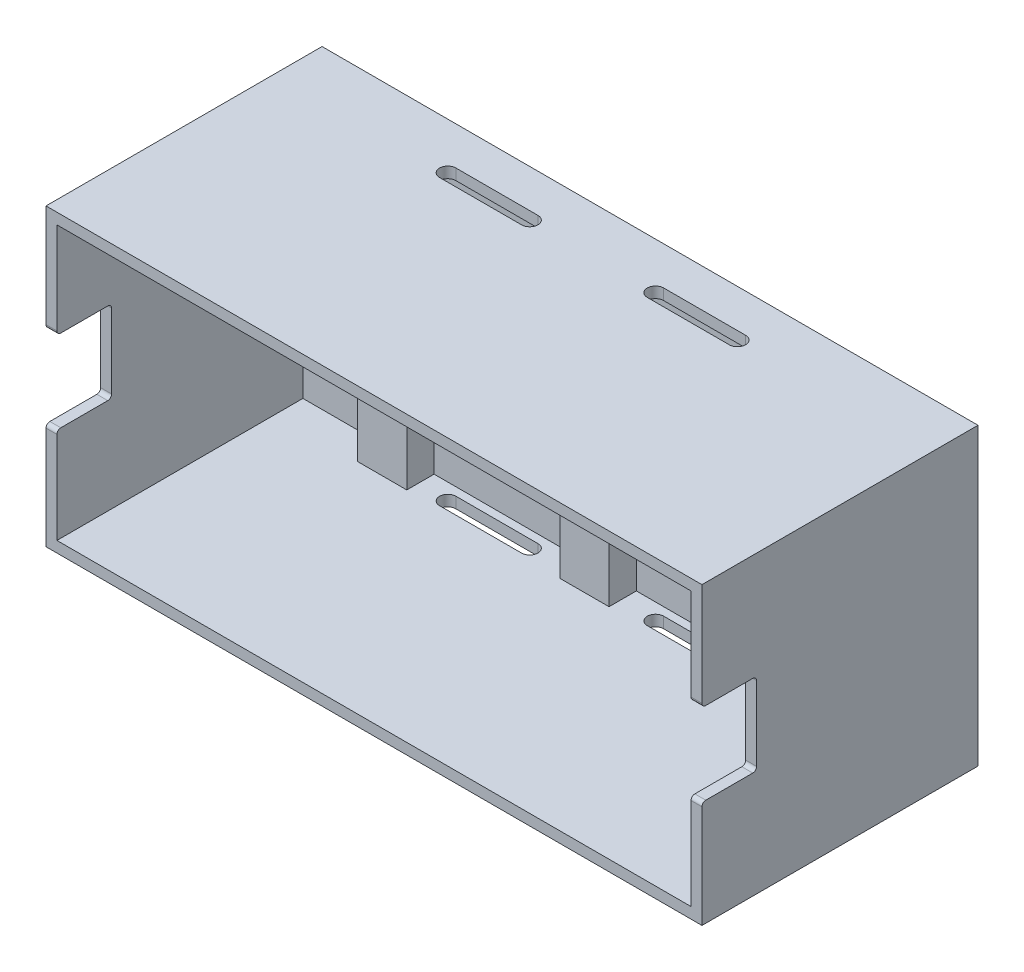
SolidWorks part; units mm, degrees
ref_plane "Front" through (0, 0, 0) normal (0, 0, 1) x (1, 0, 0)
ref_plane "Top" through (0, 0, 0) normal (0, 1, 0) x (1, 0, 0)
ref_plane "Right" through (0, 0, 0) normal (1, 0, 0) x (0, 0, -1)
sketch "Sketch1" plane through (0, 0, 0) normal (0, 0, 1) x (1, 0, 0)
  line L1 (-80.7473, 47) -> (39.2527, 47)
  line L2 (-80.7473, 47) -> (-80.7473, -7)
  line L3 (-80.7473, -7) -> (39.2527, -7)
  line L4 (39.2527, 47) -> (39.2527, -7)
  dimension "D1" = 54
  dimension "D2" = 120
extrude "Boss-Extrude1" add sketch "Sketch1" along normal blind 5.5 contours L1 L4 L3 L2
sketch "Sketch2" plane through (0, 0, 5.5) normal (0, 0, 1) x (1, 0, 0)
  line L1 (-80.7473, 47) -> (39.2527, 47)
  line L2 (-80.7473, 47) -> (-80.7473, -7)
  line L3 (-80.7473, -7) -> (39.2527, -7)
  line L4 (39.2527, 47) -> (39.2527, -7)
  line L5 (-78.7473, 45) -> (37.2527, 45)
  line L6 (-78.7473, 45) -> (-78.7473, -5)
  line L7 (-78.7473, -5) -> (37.2527, -5)
  line L8 (37.2527, 45) -> (37.2527, -5)
  dimension "D1" = 2
  dimension "D2" = 2
  dimension "D3" = 2
  dimension "D4" = 2
extrude "Boss-Extrude2" add sketch "Sketch2" along normal blind 45
sketch "Sketch3" plane through (0, 0, 5.5) normal (0, 0, 1) x (1, 0, 0)
  line L0 (37.2527, 45) -> (-78.7473, 45) construction
  line L1 (-63.7473, 45) -> (-54.7473, 45)
  line L2 (-63.7473, 45) -> (-63.7473, -5)
  line L3 (-63.7473, -5) -> (-54.7473, -5)
  line L4 (-54.7473, 45) -> (-54.7473, -5)
  line L5 (-78.7473, -5) -> (37.2527, -5) construction
  line L6 (-78.7473, -5) -> (37.2527, -5) construction
  line L7 (-26.7473, 45) -> (-17.7473, 45)
  line L8 (-26.7473, 45) -> (-26.7473, -5)
  line L9 (-26.7473, -5) -> (-17.7473, -5)
  line L10 (-17.7473, 45) -> (-17.7473, -5)
  line L11 (37.2527, 45) -> (-78.7473, 45) construction
  line L12 (10.2527, 45) -> (19.2527, 45)
  line L13 (10.2527, 45) -> (10.2527, -5)
  line L14 (10.2527, -5) -> (19.2527, -5)
  line L15 (19.2527, 45) -> (19.2527, -5)
  line L16 (37.2527, -5) -> (37.2527, 45) construction
  dimension "D1" = 9
  dimension "D2" = 9
  dimension "D3" = 9
  dimension "D4" = 18
  dimension "D5" = 28
  dimension "D6" = 28
extrude "Boss-Extrude3" add sketch "Sketch3" along normal blind 5
sketch "Sketch4" plane through (0, 0, 5.5) normal (0, 0, 1) x (1, 0, 0)
  line L2 (37.2527, 45) -> (-78.7473, 45) construction
  line L3 (37.2527, 45) -> (19.2527, 45) construction
  circle A0 centre (-4.7425, 39.5) radius 1.65
  circle A1 centre (-42.2054, 39.5) radius 1.65
  circle A3 centre (-72.6736, 39.5) radius 1.65
  circle A4 centre (29.2823, 39.5) radius 1.65
  dimension "D1" = 3.3
  dimension "D2" = 5.5
  dimension "D3" = 5.5
  dimension "D4" = 5.5
  dimension "D5" = 5.5
extrude "Cut-Extrude5" cut sketch "Sketch4" against normal blind 14
sketch "Sketch5" plane through (39.2527, 0, 0) normal (1, 0, 0) x (0, 0, -1)
  line L0 (-50.5, 27.5) -> (-40.5, 27.5)
  line L1 (-50.5, -7) -> (-50.5, 47) construction
  line L2 (-40.5, 27.5) -> (-40.5, 12.5)
  line L3 (-40.5, 12.5) -> (-50.5, 12.5)
  line L4 (-50.5, 47) -> (0, 47) construction
  line L8 (-50.5, 27.5) -> (-50.5, 12.5)
  dimension "D1" = 10
  dimension "D2" = 15
  dimension "D3" = 19.5
extrude "Cut-Extrude7" cut sketch "Sketch5" against normal through all contours L8 L3 L2 L0
fillet "Fillet1" radius 0.7 1 edges at (38.2527, 12.5, 40.5)
fillet "Fillet2" radius 0.7 1 edges at (38.2527, 27.5, 40.5)
fillet "Fillet3" radius 0.7 1 edges at (-79.7473, 12.5, 40.5)
fillet "Fillet4" radius 0.7 1 edges at (-79.7473, 27.5, 40.5)
fillet "Fillet5" radius 0.7 1 edges at (-79.7473, 12.5, 50.5)
fillet "Fillet6" radius 0.7 1 edges at (-79.7473, 27.5, 50.5)
fillet "Fillet7" radius 0.7 1 edges at (38.2527, 12.5, 50.5)
fillet "Fillet8" radius 0.7 1 edges at (38.2527, 27.5, 50.5)
sketch "Sketch6" plane through (0, -5, 0) normal (0, 1, 0) x (1, 0, 0)
  line L0 (-49.2473, -8.5) -> (-34.2473, -8.5) construction
  line L1 (-49.2473, -7) -> (-34.2473, -7)
  line L2 (-49.2473, -10) -> (-34.2473, -10)
  line L3 (-11.2473, -8.5) -> (3.7527, -8.5) construction
  line L4 (-11.2473, -7) -> (3.7527, -7)
  line L5 (-11.2473, -10) -> (3.7527, -10)
  line L6 (-78.7473, -5.5) -> (-63.7473, -5.5) construction
  line L7 (-78.7473, -50.5) -> (-78.7473, -5.5) construction
  line L8 (37.2527, -50.5) -> (37.2527, -5.5) construction
  arc A0 (-49.2473, -7) -> (-49.2473, -10) centre (-49.2473, -8.5) ccw
  arc A1 (-34.2473, -10) -> (-34.2473, -7) centre (-34.2473, -8.5) ccw
  arc A2 (-11.2473, -7) -> (-11.2473, -10) centre (-11.2473, -8.5) ccw
  arc A3 (3.7527, -10) -> (3.7527, -7) centre (3.7527, -8.5) ccw
  point P2 (-41.7473, -8.5)
  point P7 (-3.7473, -8.5)
  dimension "D1" = 15
  dimension "D2" = 3
  dimension "D3" = 3
  dimension "D4" = 37
  dimension "D5" = 41
extrude "Cut-Extrude8" cut sketch "Sketch6" against normal through all both and the other way through all
sketch "Sketch7" plane through (0, 0, 0) normal (0, 0, -1) x (-1, 0, 0)
  line L1 (-39.2527, -7) -> (-31.2527, -7)
  line L2 (-39.2527, -7) -> (-39.2527, 1)
  line L3 (-39.2527, 1) -> (-31.2527, 1)
  line L4 (-31.2527, -7) -> (-31.2527, 1)
  line L5 (80.7473, -7) -> (72.7473, -7)
  line L6 (80.7473, -7) -> (80.7473, 1)
  line L7 (80.7473, 1) -> (72.7473, 1)
  line L8 (72.7473, -7) -> (72.7473, 1)
  dimension "D1" = 8
